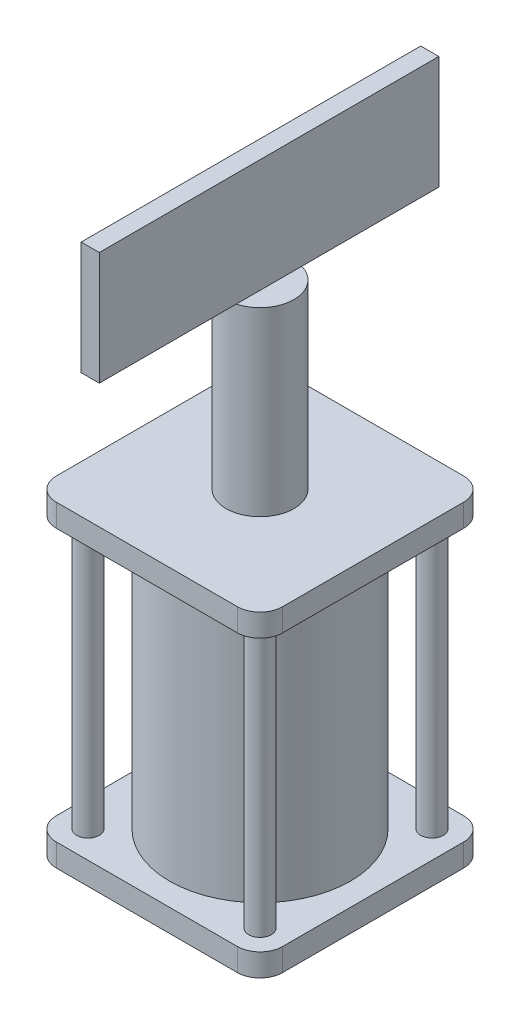
SolidWorks part; units mm, degrees
ref_plane "Front Plane" through (0, 0, 0) normal (0, 0, 1) x (1, 0, 0)
ref_plane "Top Plane" through (0, 0, 0) normal (0, 1, 0) x (1, 0, 0)
ref_plane "Right Plane" through (0, 0, 0) normal (1, 0, 0) x (0, 0, -1)
sketch "Sketch1" plane through (0, 0, 0) normal (0, 1, 0) x (1, 0, 0)
  line L1 (-50, -50) -> (50, -50)
  line L2 (-50, -50) -> (-50, 50)
  line L3 (-50, 50) -> (50, 50)
  line L4 (50, -50) -> (50, 50)
  line L5 (-50, -50) -> (50, 50) construction
  line L6 (-50, 50) -> (50, -50) construction
  point P0 (0, 0)
  dimension "D1" = 100
  dimension "D2" = 100
extrude "Boss-Extrude1" add sketch "Sketch1" along normal blind 10
sketch "Sketch2" plane through (0, 10, 0) normal (0, 1, 0) x (1, 0, 0)
  circle A0 centre (0, 0) radius 40
  dimension "D1" = 80
extrude "Boss-Extrude2" add sketch "Sketch2" along normal blind 120 separate body
sketch "Sketch3" plane through (0, 130, 0) normal (0, 1, 0) x (1, 0, 0)
  line L1 (-50, 50) -> (50, 50)
  line L2 (-50, 50) -> (-50, -50)
  line L3 (-50, -50) -> (50, -50)
  line L4 (50, 50) -> (50, -50)
extrude "Boss-Extrude3" add sketch "Sketch3" along normal blind 10 separate body
sketch "Sketch4" plane through (0, 140, 0) normal (0, 1, 0) x (1, 0, 0)
  circle A0 centre (0, 0) radius 15
  dimension "D1" = 30
extrude "Boss-Extrude4" add sketch "Sketch4" along normal blind 80 separate body
sketch "Sketch5" plane through (0, 10, 0) normal (0, 1, 0) x (1, 0, 0)
  line L0 (-50, 50) -> (-50, -50) construction
  line L1 (50, 50) -> (-50, 50) construction
  line L2 (0, 50) -> (0, 0) construction
  line L3 (0, 0) -> (50, 0) construction
  line L4 (50, -50) -> (50, 50) construction
  circle A0 centre (-38, 38) radius 5
  circle A1 centre (38, 38) radius 5
  circle A2 centre (38, -38) radius 5
  circle A3 centre (-38, -38) radius 5
  dimension "D1" = 10
  dimension "D2" = 12
  dimension "D3" = 12
extrude "Boss-Extrude5" add sketch "Sketch5" along normal up to surface (120 mm away) up to face at (0, 130, 0)
fillet "Fillet1" radius 10 8 edges at (50, 5, -50) (50, 5, 50) (-50, 5, 50) (-50, 5, -50) (-50, 135, -50) (50, 135, -50) (50, 135, 50) (-50, 135, 50)
sketch "Sketch6" plane through (0, 220, 0) normal (0, 1, 0) x (1, 0, 0)
  line L1 (-4, -75) -> (4, -75)
  line L2 (-4, -75) -> (-4, 75)
  line L3 (-4, 75) -> (4, 75)
  line L4 (4, -75) -> (4, 75)
  line L5 (-4, -75) -> (4, 75) construction
  line L6 (-4, 75) -> (4, -75) construction
  point P0 (0, 0)
  dimension "D1" = 150
  dimension "D2" = 8
extrude "Boss-Extrude6" add sketch "Sketch6" along normal blind 50 separate body
